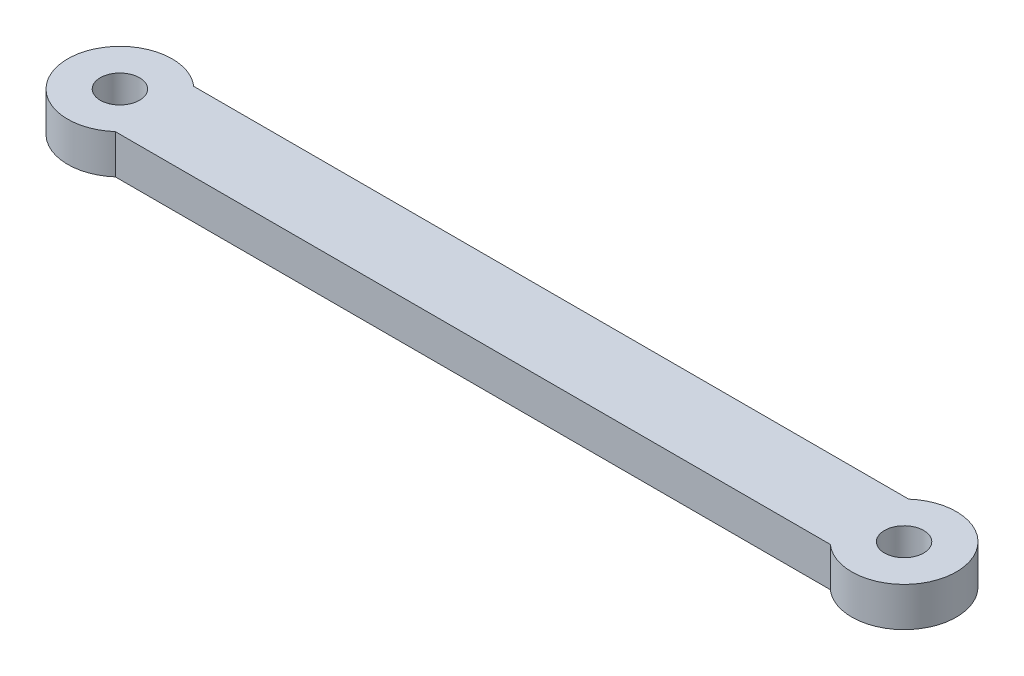
SolidWorks part; units mm, degrees
ref_plane "Alzado" through (0, 0, 0) normal (0, 0, 1) x (1, 0, 0)
ref_plane "Planta" through (0, 0, 0) normal (0, 1, 0) x (1, 0, 0)
ref_plane "Vista lateral" through (0, 0, 0) normal (1, 0, 0) x (0, 0, -1)
sketch "Croquis1" plane through (0, 0, 0) normal (0, 1, 0) x (1, 0, 0)
  line L0 (-27.3542, 3) -> (27.3542, 3)
  line L2 (27.3542, -3) -> (-27.3542, -3)
  circle A0 centre (-30, 0) radius 1.5
  arc A1 (-27.3542, 3) -> (-27.3542, -3) centre (-30, 0) ccw
  circle A2 centre (30, 0) radius 1.5
  arc A3 (27.3542, 3) -> (27.3542, -3) centre (30, 0) cw
  dimension "D1" = 3
  dimension "D2" = 8
  dimension "D6" = 4
  dimension "D9" = 3
  dimension "D3" = 3
  dimension "D4" = 3
  dimension "D5" = 60
  dimension "D7" = 30
extrude "Saliente-Extruir1" add sketch "Croquis1" along normal blind 3
